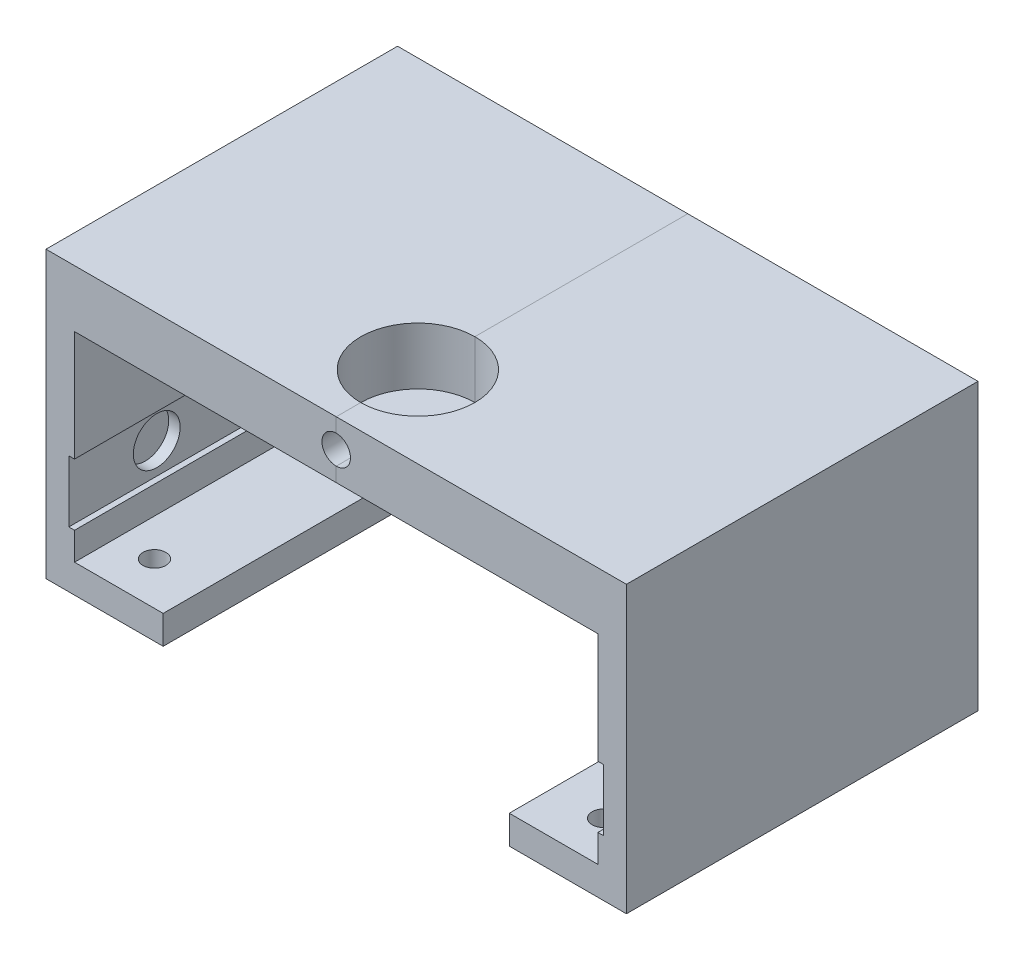
SolidWorks part; units mm, degrees
ref_plane "Front Plane" through (0, 0, 0) normal (0, 0, 1) x (1, 0, 0)
ref_plane "Top Plane" through (0, 0, 0) normal (0, 1, 0) x (1, 0, 0)
ref_plane "Right Plane" through (0, 0, 0) normal (1, 0, 0) x (0, 0, -1)
sketch "Croquis1" plane through (0, 0, 0) normal (0, 1, 0) x (1, 0, 0)
  line L0 (-45.85, 14.3) -> (-45.85, 47.3)
  line L1 (45.85, -14.3) -> (-45.85, -14.3)
  line L2 (45.85, -14.3) -> (45.85, 14.3)
  line L4 (-45.85, -14.3) -> (-45.85, 14.3)
  line L5 (45.85, -14.3) -> (-45.85, 14.3) construction
  line L6 (45.85, 14.3) -> (-45.85, -14.3) construction
  line L7 (-45.85, 47.3) -> (45.85, 47.3)
  line L8 (45.85, 47.3) -> (45.85, 14.3)
  point P0 (0, 0)
  dimension "D1" = 91.7
  dimension "D2" = 28.6
  dimension "D3" = 33
extrude "Saliente-Extruir1" add sketch "Croquis1" along normal blind 10
sketch "Croquis3" plane through (0, 10, 0) normal (0, 1, 0) x (1, 0, 0)
  circle A0 centre (0, 0) radius 10
  dimension "D1" = 20
extrude "Cortar-Extruir1" cut sketch "Croquis3" against normal blind 10
sketch "Croquis4" plane through (0, 0, 14.3) normal (0, 0, 1) x (1, 0, 0)
  line L0 (-45.85, 0) -> (45.85, 10) construction
  circle A0 centre (0, 5) radius 2.5
  dimension "D1" = 5
extrude "Cortar-Extruir2" cut sketch "Croquis4" against normal blind 10
sketch "Croquis6" plane through (0, 10, 0) normal (0, 1, 0) x (1, 0, 0)
  line L0 (-45.85, 47.3) -> (-50.85, 47.3)
  line L1 (-45.85, 47.3) -> (-45.85, -14.3)
  line L2 (-45.85, -14.3) -> (-50.85, -14.3)
  line L3 (-50.85, -14.3) -> (-50.85, 47.3)
  line L4 (0, 47.3) -> (0, -14.3) construction
  line L5 (45.85, 47.3) -> (-45.85, 47.3) construction
  line L6 (-45.85, -14.3) -> (45.85, -14.3) construction
  line L7 (45.85, -14.3) -> (50.85, -14.3)
  line L8 (45.85, 47.3) -> (45.85, -14.3)
  line L9 (45.85, 47.3) -> (50.85, 47.3)
  line L10 (50.85, -14.3) -> (50.85, 47.3)
  dimension "D1" = 5
extrude "Saliente-Extruir2" add sketch "Croquis6" against normal blind 50
sketch "Croquis7" plane through (0, -40, 0) normal (0, -1, 0) x (1, 0, 0)
  line L0 (-45.85, 14.3) -> (-30.3207, 14.3)
  line L1 (-30.3207, 14.3) -> (-30.3207, -47.3)
  line L2 (45.85, -47.3) -> (-45.85, -47.3) construction
  line L3 (-30.3207, -47.3) -> (-45.85, -47.3)
  line L4 (-45.85, -47.3) -> (-45.85, 14.3)
  line L5 (0, 14.3) -> (0, -47.3) construction
  line L6 (-45.85, 14.3) -> (45.85, 14.3) construction
  line L7 (30.3207, -47.3) -> (45.85, -47.3)
  line L8 (30.3207, 14.3) -> (30.3207, -47.3)
  line L9 (45.85, 14.3) -> (30.3207, 14.3)
  line L10 (45.85, -47.3) -> (45.85, 14.3)
extrude "Saliente-Extruir3" add sketch "Croquis7" against normal blind 5
sketch "Croquis8" plane through (0, -40, 0) normal (0, -1, 0) x (1, 0, 0)
  line L0 (-50.85, -47.3) -> (-50.85, 6.8) construction
  line L1 (-50.85, -47.3) -> (-50.85, 14.3) construction
  line L2 (-50.85, 6.8) -> (-39.35, 6.8) construction
  line L3 (0, 14.3) -> (0, -47.3) construction
  line L4 (-45.85, 14.3) -> (45.85, 14.3) construction
  line L5 (45.85, -47.3) -> (-45.85, -47.3) construction
  circle A0 centre (-39.35, 6.8) radius 2
  circle A1 centre (39.35, 6.8) radius 2
  dimension "D1" = 4
extrude "Cortar-Extruir3" cut sketch "Croquis8" against normal blind 10
sketch "Croquis9" plane through (0, 0, 14.3) normal (0, 0, 1) x (1, 0, 0)
  line L0 (-45.85, -35) -> (-45.85, -30.15) construction
  line L1 (-45.85, -35) -> (-45.85, 0) construction
  line L2 (-45.85, -30.15) -> (-46.85, -30.15)
  line L3 (-46.85, -30.15) -> (-46.85, -19.35)
  line L4 (-46.85, -19.35) -> (-45.85, -19.35)
  line L5 (-45.85, -19.35) -> (-45.85, -30.15)
  line L6 (0, 10) -> (0, -38.2051) construction
  line L7 (-50.85, 10) -> (50.85, 10) construction
  line L8 (46.85, -19.35) -> (45.85, -19.35)
  line L9 (46.85, -30.15) -> (46.85, -19.35)
  line L10 (45.85, -30.15) -> (46.85, -30.15)
  line L11 (45.85, -19.35) -> (45.85, -30.15)
  line L12 (-45.85, -24.75) -> (-50.85, -24.75) construction
  line L13 (-50.85, -40) -> (-50.85, 10) construction
  line L14 (-45.85, -35) -> (-50.85, -35) construction
  line L15 (-50.85, -24.75) -> (-50.85, -35) construction
  dimension "D1" = 10.8
  dimension "D2" = 10.25
extrude "Cortar-Extruir4" cut sketch "Croquis9" against normal blind 100
sketch "Croquis11" plane through (-46.85, 0, 0) normal (1, 0, 0) x (0, 0, -1)
  line L0 (16.5, -19.35) -> (16.5, -30.15) construction
  line L3 (47.3, -19.35) -> (-14.3, -19.35) construction
  line L4 (47.3, -30.15) -> (-14.3, -30.15) construction
  line L6 (-14.3, -24.75) -> (16.5, -24.75) construction
  line L7 (-14.3, -19.35) -> (-14.3, -30.15) construction
  circle A0 centre (1.1, -24.75) radius 4.1039
  circle A1 centre (31.9, -24.75) radius 4.1039
extrude "Cortar-Extruir5" cut sketch "Croquis11" against normal blind 2 and the other way blind 95.7
split "Partir1" trim tools "Right Plane" bodies to split 108 resulting bodies 109 110
